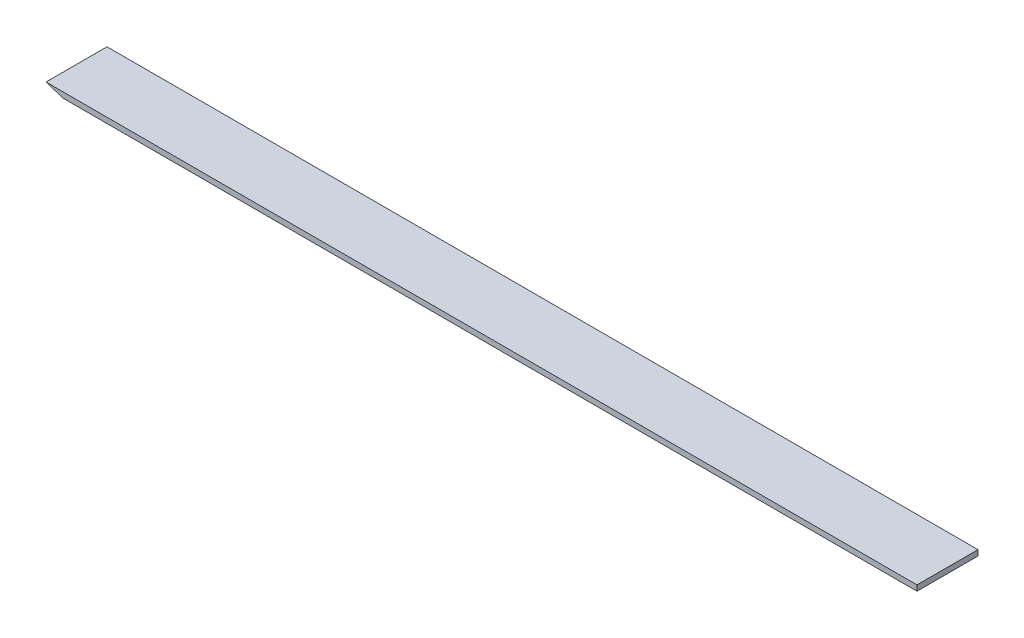
SolidWorks part; units mm, degrees
ref_plane "Front Plane" through (0, 0, 0) normal (0, 0, 1) x (1, 0, 0)
ref_plane "Top Plane" through (0, 0, 0) normal (0, 1, 0) x (1, 0, 0)
ref_plane "Right Plane" through (0, 0, 0) normal (1, 0, 0) x (0, 0, -1)
sketch "Sketch1" plane through (0, 0, 0) normal (0, 0, 1) x (1, 0, 0)
  line L0 (0, 0) -> (1428, 0)
  line L1 (1428, 0) -> (1428, -9)
  line L2 (1428, -9) -> (28, -9)
  line L3 (28, -9) -> (0, 0)
  dimension "D1" = 9
  dimension "D2" = 1400
  dimension "D3" = 28
extrude "Boss-Extrude1" add sketch "Sketch1" along normal blind 100 contours L3 L0 L1 L2
